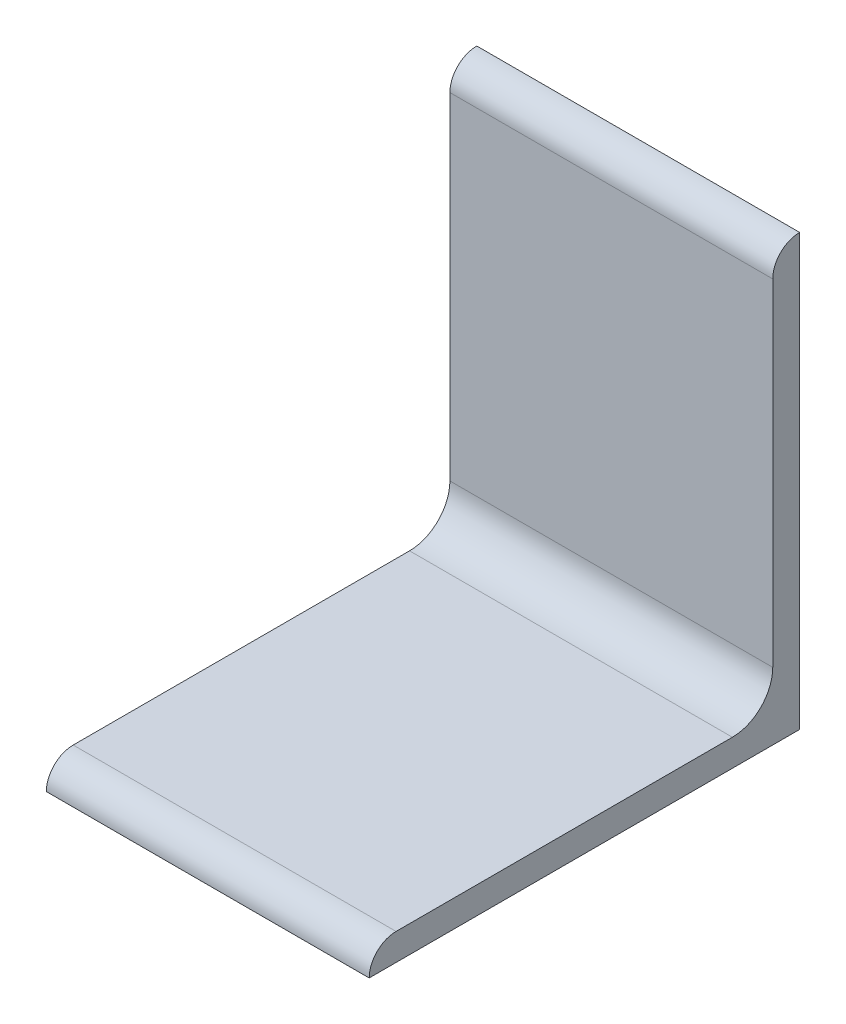
SolidWorks part; units mm, degrees
ref_plane "Alzado" through (0, 0, 0) normal (0, 0, 1) x (1, 0, 0)
ref_plane "Planta" through (0, 0, 0) normal (0, 1, 0) x (1, 0, 0)
ref_plane "Vista lateral" through (0, 0, 0) normal (1, 0, 0) x (0, 0, -1)
sketch "Croquis1" plane through (0, 0, 0) normal (0, 0, 1) x (1, 0, 0)
  line L0 (0, 0) -> (38.1, 0)
  dimension "D1" = 38.1
other "Hierro angular 2 X 2 X 0.125(1)"
ref_plane "Plano1" through (0, 0, 0) normal (1, 0, 0) x (0, 1, 0)
sketch "Sketch12" plane through (0, 0, 0) normal (1, 0, 0) x (0, 1, 0)
  line L0 (0, 0) -> (0, 50.8)
  line L1 (0, 50.8) -> (0.0051, 50.8)
  line L2 (3.175, 47.6301) -> (3.175, 7.9375)
  line L3 (7.9375, 3.175) -> (47.6301, 3.175)
  line L4 (50.8, 0.0051) -> (50.8, 0)
  line L5 (50.8, 0) -> (0, 0)
  arc A0 (50.8, 0.0051) -> (47.6301, 3.175) centre (47.6301, 0.0051) ccw
  arc A1 (0.0051, 50.8) -> (3.175, 47.6301) centre (0.0051, 47.6301) cw
  arc A2 (7.9375, 3.175) -> (3.175, 7.9375) centre (7.9375, 7.9375) cw
  point P10 (25.4, 0)
  point P14 (0, 25.4)
  point P15 (3.175, 25.4)
  point P16 (25.4, 3.175)
  point P17 (3.175, 50.8)
  point P18 (50.8, 3.175)
  point P19 (0, 0)
  dimension "D2" = 0.0051
  dimension "Radius_1" = 4.7625
  dimension "D1" = 3.175
  dimension "H_leg" = 50.8
